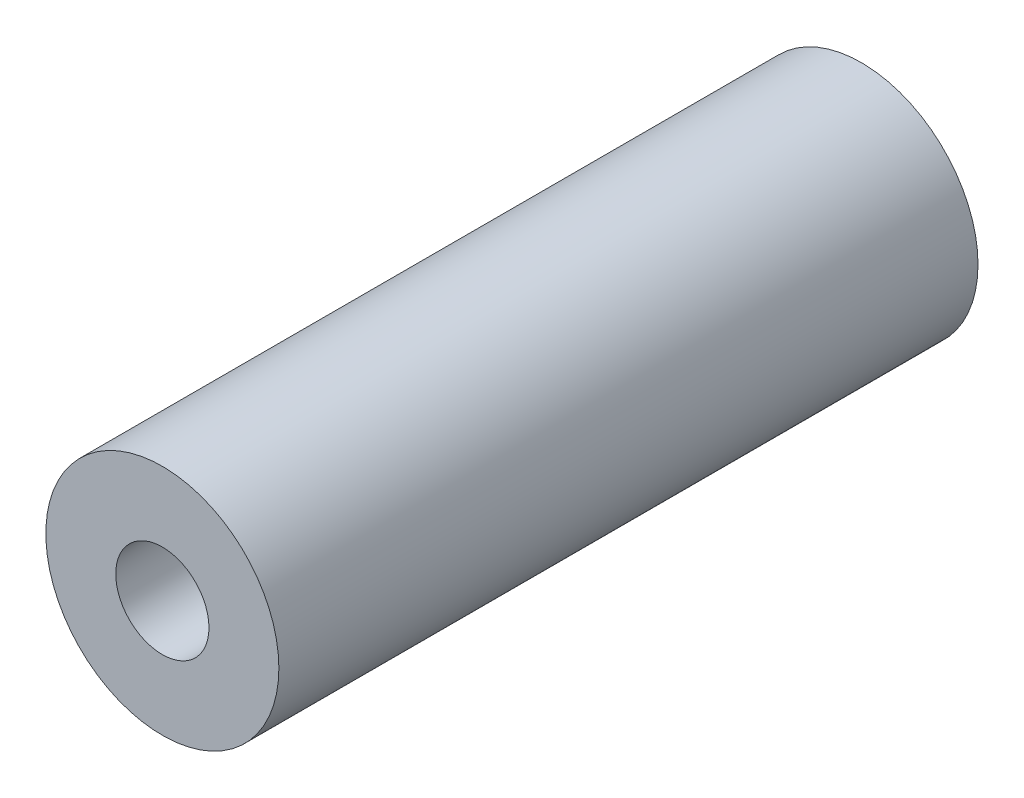
SolidWorks part; units mm, degrees
ref_plane "Front Plane" through (0, 0, 0) normal (0, 0, 1) x (1, 0, 0)
ref_plane "Top Plane" through (0, 0, 0) normal (0, 1, 0) x (1, 0, 0)
ref_plane "Right Plane" through (0, 0, 0) normal (1, 0, 0) x (0, 0, -1)
sketch "Standoff_OD8_ID3p2_profile" plane through (0, 0, 0) normal (0, 0, 1) x (1, 0, 0)
  circle A0 centre (0, 0) radius 4
  circle A1 centre (0, 0) radius 1.6
extrude "Standoff_OD8_ID3p2" add sketch "Standoff_OD8_ID3p2_profile" along normal blind 24
